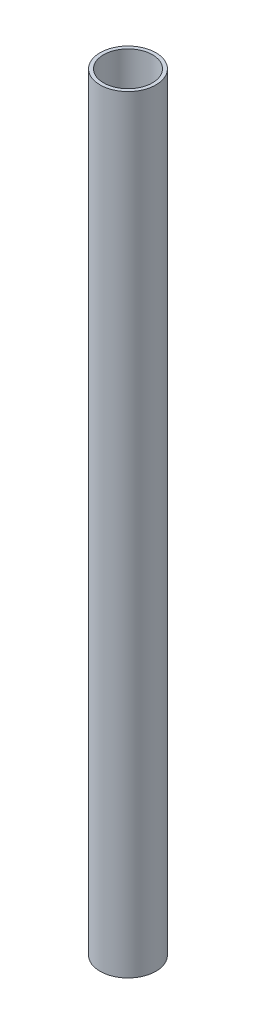
SolidWorks part; units mm, degrees
ref_plane "Front Plane" through (0, 0, 0) normal (0, 0, 1) x (1, 0, 0)
ref_plane "Top Plane" through (0, 0, 0) normal (0, 1, 0) x (1, 0, 0)
ref_plane "Right Plane" through (0, 0, 0) normal (1, 0, 0) x (0, 0, -1)
sketch "Sketch1" plane through (0, 0, 0) normal (0, 1, 0) x (1, 0, 0)
  circle A0 centre (0, 0) radius 50.8
  circle A1 centre (0, 0) radius 44.45
  dimension "D1" = 101.6
  dimension "D2" = 88.9
extrude "Boss-Extrude1" add sketch "Sketch1" along normal blind 1397
